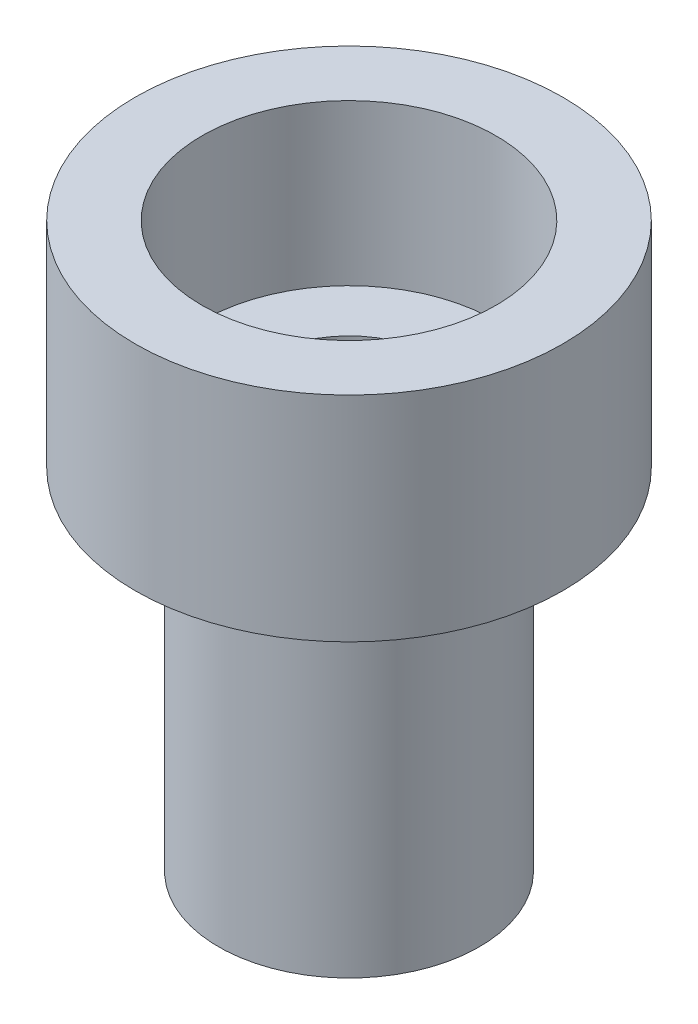
SolidWorks part; units mm, degrees
ref_plane "Front Plane" through (0, 0, 0) normal (0, 0, 1) x (1, 0, 0)
ref_plane "Top Plane" through (0, 0, 0) normal (0, 1, 0) x (1, 0, 0)
ref_plane "Right Plane" through (0, 0, 0) normal (1, 0, 0) x (0, 0, -1)
sketch "Sketch1" plane through (0, 0, 0) normal (0, 1, 0) x (1, 0, 0)
  circle A0 centre (0, 0) radius 4
  dimension "D1" = 8
extrude "Boss-Extrude1" add sketch "Sketch1" along normal blind 4
sketch "Sketch2" plane through (0, 0, 0) normal (0, -1, 0) x (1, 0, 0)
  circle A0 centre (0, 0) radius 2.44
  dimension "D1" = 4.88
extrude "Boss-Extrude2" add sketch "Sketch2" along normal blind 6.55
sketch "Sketch3" plane through (0, 4, 0) normal (0, 1, 0) x (1, 0, 0)
  circle A0 centre (0, 0) radius 2.75
  dimension "D1" = 5.5
extrude "Cut-Extrude1" cut sketch "Sketch3" against normal blind 3
sketch "Sketch4" plane through (0, 1, 0) normal (0, 1, 0) x (1, 0, 0)
  circle A0 centre (0, 0) radius 1.6
  dimension "D1" = 3.2
extrude "Cut-Extrude2" cut sketch "Sketch4" against normal through all
